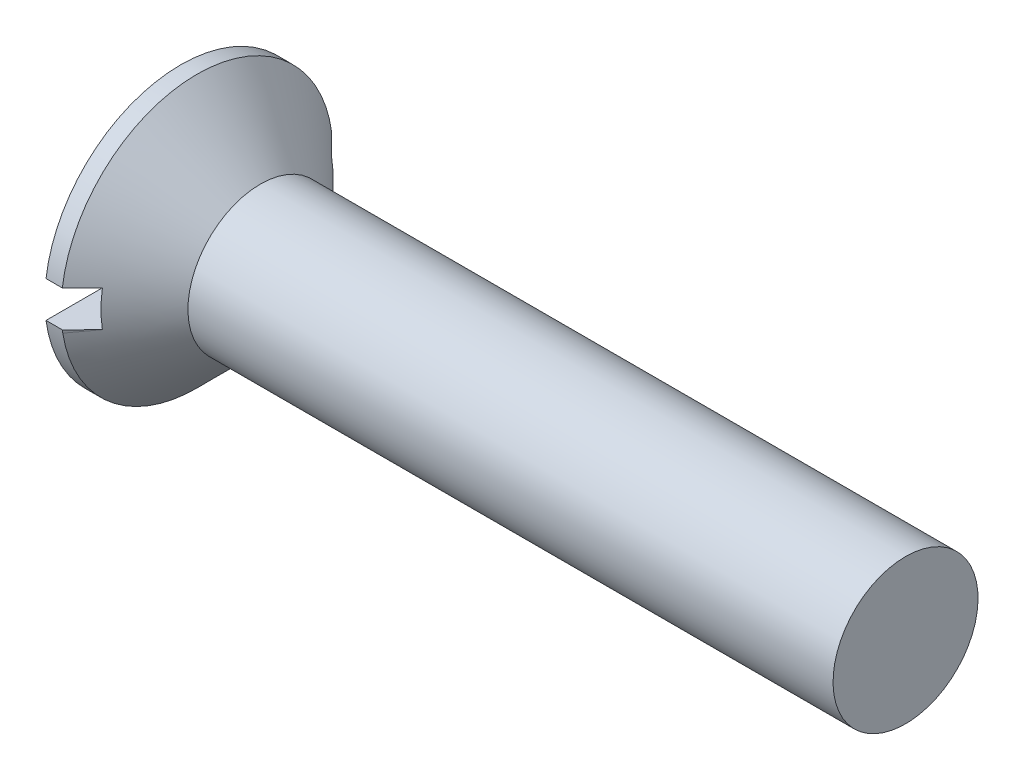
SolidWorks part; units mm, degrees
material "Plain Carbon Steel"
ref_plane "Front Plane" through (0, 0, 0) normal (0, 0, 1) x (1, 0, 0)
ref_plane "Top Plane" through (0, 0, 0) normal (0, 1, 0) x (1, 0, 0)
ref_plane "Right Plane" through (0, 0, 0) normal (1, 0, 0) x (0, 0, -1)
sketch "Sketch1" plane through (0, 0, 0) normal (0, 0, 1) x (1, 0, 0)
  line L0 (0, 0) -> (0, 3.75)
  line L1 (0, 3.75) -> (0.45, 3.75)
  line L2 (0.45, 3.75) -> (2.2, 2)
  line L3 (2.2, 2) -> (20, 2)
  line L4 (20, 2) -> (20, 0)
  line L5 (20, 0) -> (0, 0) construction
  line L6 (0, 0) -> (20, 0)
  dimension "D1" = 45
  dimension "D2" = 4
  dimension "D3" = 7.5
  dimension "D4" = 2.2
  dimension "D5" = 20
revolve "Revolve1" add sketch "Sketch1" angle 360 about L5
sketch "Sketch2" plane through (0, 0, 0) normal (-1, 0, 0) x (0, 0, 1)
  line L0 (3.75, 0) -> (-3.75, 0) construction
  line L1 (-3.75, 0.5) -> (3.75, 0.5)
  line L2 (-3.75, 0.5) -> (-3.75, -0.5)
  line L3 (-3.75, -0.5) -> (3.75, -0.5)
  line L4 (3.75, 0.5) -> (3.75, -0.5)
  circle A0 centre (0, 0) radius 3.75 construction
  dimension "D1" = 1
extrude "Cut-Extrude1" cut sketch "Sketch2" against normal blind 1
